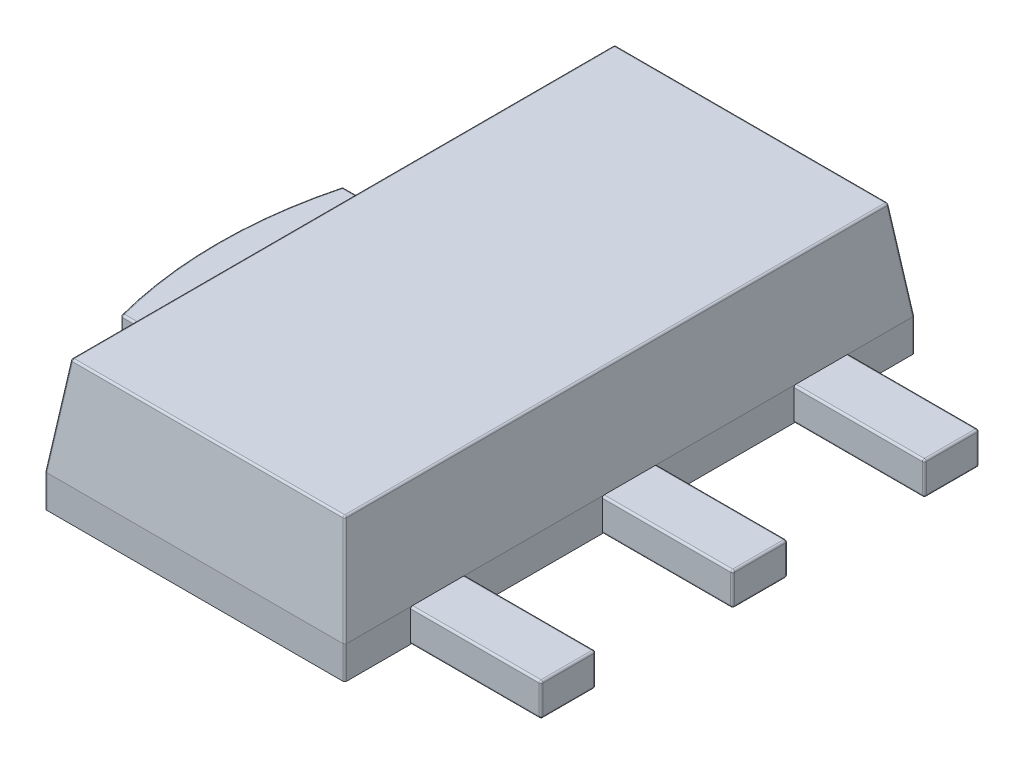
SolidWorks part; units mm, degrees
ref_plane "Front Plane" through (0, 0, 0) normal (0, 0, 1) x (1, 0, 0)
ref_plane "Top Plane" through (0, 0, 0) normal (0, 1, 0) x (1, 0, 0)
ref_plane "Right Plane" through (0, 0, 0) normal (1, 0, 0) x (0, 0, -1)
sketch "Sketch1" plane through (0, 0, 0) normal (0, 1, 0) x (1, 0, 0)
  line L1 (-1.15, -2.185) -> (1.15, -2.185)
  line L2 (-1.15, -2.185) -> (-1.15, 2.185)
  line L3 (-1.15, 2.185) -> (1.15, 2.185)
  line L4 (1.15, -2.185) -> (1.15, 2.185)
  line L5 (-1.15, -2.185) -> (1.15, 2.185) construction
  line L6 (-1.15, 2.185) -> (1.15, -2.185) construction
  point P0 (0, 0)
  dimension "D1" = 2.3
  dimension "D2" = 4.37
extrude "Boss-Extrude1" add sketch "Sketch1" along normal mid plane 1
sketch "Sketch2" plane through (0, 0, 2.185) normal (0, 0, 1) x (1, 0, 0)
  line L0 (-1.15, -0.25) -> (1.15, -0.25) construction
  line L1 (-1.15, 0.5) -> (-1.15, -0.5) construction
  line L2 (1.15, 0.5) -> (1.15, -0.5) construction
  line L3 (-1.15, -0.5) -> (1.15, -0.5) construction
  line L4 (-1.15, -0.25) -> (-1.15, 0.5)
  line L5 (-1.15, 0.5) -> (-1.05, 0.5)
  line L6 (-1.15, 0.5) -> (1.15, 0.5) construction
  line L7 (-1.05, 0.5) -> (-1.15, -0.25)
  line L8 (0, -0.25) -> (0, 0.5) construction
  line L9 (1.05, 0.5) -> (1.15, -0.25)
  line L10 (1.15, 0.5) -> (1.05, 0.5)
  line L11 (1.15, -0.25) -> (1.15, 0.5)
  dimension "D1" = 0.25
  dimension "D2" = 0.1
extrude "Cut-Extrude1" cut sketch "Sketch2" against normal through all
sketch "Sketch3" plane through (1.15, 0, 0) normal (1, 0, 0) x (0, 0, -1)
  line L0 (-2.185, -0.25) -> (-2.185, 0.5)
  line L1 (-2.185, 0.5) -> (-2.085, 0.5)
  line L2 (2.185, 0.5) -> (-2.185, 0.5) construction
  line L3 (-2.085, 0.5) -> (-2.185, -0.25)
  line L4 (0, 0) -> (0, 1.1486) construction
  line L5 (2.085, 0.5) -> (2.185, -0.25)
  line L6 (2.185, 0.5) -> (2.085, 0.5)
  line L7 (2.185, -0.25) -> (2.185, 0.5)
  dimension "D1" = 0.1
extrude "Cut-Extrude2" cut sketch "Sketch3" against normal through all
fillet "Fillet1" radius 0.015 12 edges at (0, 0.5, -2.085) (1.05, 0.5, 0) (0, 0.5, 2.085) (-1.05, 0.5, 0) (-1.15, -0.375, 2.185) (-1.1, 0.125, 2.135) (-1.15, -0.375, -2.185) (-1.1, 0.125, -2.135) (1.15, -0.375, -2.185) (1.1, 0.125, -2.135) (1.1, 0.125, 2.135) (1.15, -0.375, 2.185)
sketch "Sketch6" plane through (0, -0.5, 0) normal (0, -1, 0) x (1, 0, 0)
  line L0 (-1.15, -2.17) -> (-1.15, 2.17) construction
  line L5 (-1.15, 0.85) -> (-1.9, -0.85) construction
  line L6 (-1.15, -0.85) -> (-1.9, 0.85) construction
  line L7 (1.15, -2.17) -> (1.15, 2.17) construction
  line L12 (1.15, 0.21) -> (2.15, -0.21) construction
  line L13 (1.15, -0.21) -> (2.15, 0.21) construction
  line L14 (1.15, 1.68) -> (1.15, 1.26)
  line L15 (1.15, 1.68) -> (2.15, 1.68)
  line L16 (2.15, 1.68) -> (2.15, 1.26)
  line L17 (1.15, 1.26) -> (2.15, 1.26)
  line L18 (1.15, 0.21) -> (1.15, -0.21)
  line L19 (1.15, 0.21) -> (2.15, 0.21)
  line L20 (2.15, 0.21) -> (2.15, -0.21)
  line L21 (1.15, -0.21) -> (2.15, -0.21)
  line L22 (1.15, -1.26) -> (1.15, -1.68)
  line L23 (1.15, -1.26) -> (2.15, -1.26)
  line L24 (2.15, -1.26) -> (2.15, -1.68)
  line L25 (1.15, -1.68) -> (2.15, -1.68)
  line L26 (-1.9, 0.85) -> (-1.15, 0.85)
  line L27 (-1.15, 0.85) -> (-1.15, -0.85)
  line L28 (-1.9, -0.85) -> (-1.15, -0.85)
  arc A0 (-1.9, 0.85) -> (-1.9, -0.85) centre (1.2887, 0) ccw
  point P4 (-1.525, 0)
  point P13 (1.65, 0)
  dimension "D3" = 3.3
  dimension "D1" = 0.75
  dimension "D2" = 1.7
  dimension "D4" = 1
  dimension "D5" = 0.42
extrude "Boss-Extrude2" add sketch "Sketch6" against normal blind 0.25
fillet "Fillet2" radius 0.015 32 edges at (2.15, -0.375, 1.68) (2.15, -0.25, 1.47) (2.15, -0.375, 1.26) (2.15, -0.5, 1.47) (-1.525, -0.5, 0.85) (-1.525, -0.25, 0.85) (-1.9, -0.375, 0.85) (-2.0113, -0.5, 0) (-2.0113, -0.25, 0) (-1.525, -0.5, -0.85) (-1.525, -0.25, -0.85) (-1.9, -0.375, -0.85) (1.65, -0.5, -1.26) (1.65, -0.25, -1.26) (2.15, -0.5, -1.47) (2.15, -0.25, -1.47) (1.65, -0.5, -1.68) (1.65, -0.25, -1.68) (2.15, -0.375, -1.68) (2.15, -0.375, -1.26) (1.65, -0.5, -0.21) (1.65, -0.25, -0.21) (2.15, -0.5, 0) (2.15, -0.25, 0) (2.15, -0.375, -0.21) (2.15, -0.375, 0.21) (1.65, -0.5, 0.21) (1.65, -0.25, 0.21) (1.65, -0.5, 1.68) (1.65, -0.25, 1.68) (1.65, -0.25, 1.26) (1.65, -0.5, 1.26)
